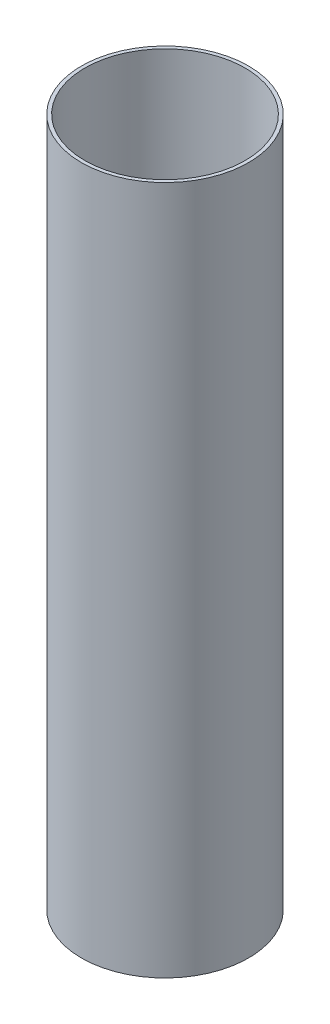
SolidWorks part; units mm, degrees
ref_plane "Front" through (0, 0, 0) normal (0, 0, 1) x (1, 0, 0)
ref_plane "Top" through (0, 0, 0) normal (0, 1, 0) x (1, 0, 0)
ref_plane "Right" through (0, 0, 0) normal (1, 0, 0) x (0, 0, -1)
sketch "Croquis1" plane through (0, 0, 0) normal (0, 1, 0) x (1, 0, 0)
  circle A0 centre (0, 0) radius 85
  dimension "D1" = 170
extrude "Saliente-Extruir1" add sketch "Croquis1" along normal blind 700
shell "Vaciado1" thickness 3.5
